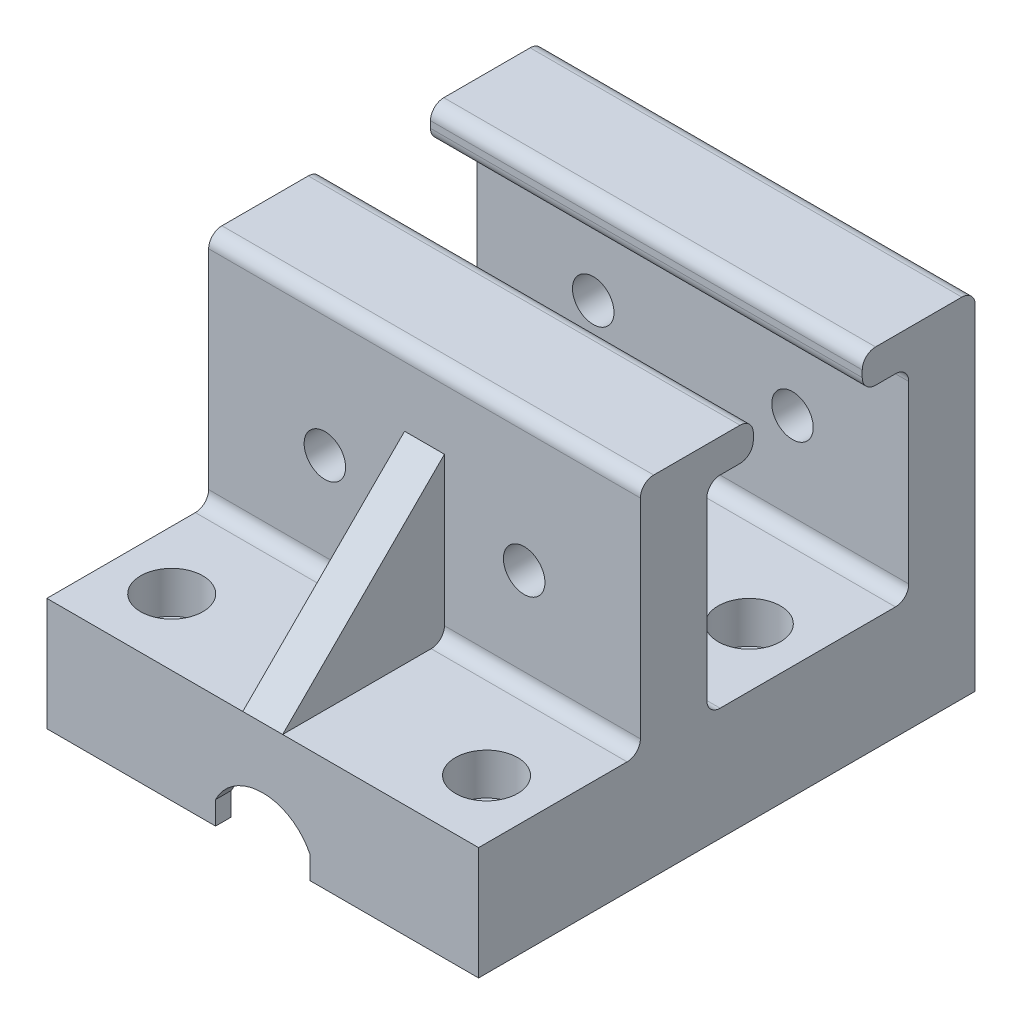
SolidWorks part; units mm, degrees
ref_plane "Front Plane" through (0, 0, 0) normal (0, 0, 1) x (1, 0, 0)
ref_plane "Top Plane" through (0, 0, 0) normal (0, 1, 0) x (1, 0, 0)
ref_plane "Right Plane" through (0, 0, 0) normal (1, 0, 0) x (0, 0, -1)
sketch "Sketch1" plane through (0, 0, 0) normal (0, 0, 1) x (1, 0, 0)
  line L0 (0, 0) -> (0, 28.1718) construction
  line L1 (15.875, 0) -> (41.275, 0)
  line L2 (41.275, 0) -> (41.275, 21.59)
  line L3 (41.275, 21.59) -> (-41.275, 21.59)
  line L4 (-41.275, 0) -> (-41.275, 21.59)
  line L5 (-15.875, 0) -> (-41.275, 0)
  arc A0 (15.875, 0) -> (-15.875, 0) centre (0, 0) ccw
  point P9 (0, 21.59)
  dimension "D1" = 31.75
  dimension "D2" = 25.4
  dimension "D3" = 21.59
extrude "Boss-Extrude1" add sketch "Sketch1" along normal blind 94.9452
sketch "Sketch2" plane through (0, 0, 0) normal (0, 0, -1) x (-1, 0, 0)
  circle A0 centre (0, 0) radius 18.923
  dimension "D1" = 37.846
extrude "Cut-Extrude1" cut sketch "Sketch2" against normal blind 56.9976
sketch "Sketch3" plane through (0, 0, 94.9452) normal (0, 0, 1) x (1, 0, 0)
  line L0 (-9.017, 4.3994) -> (-9.017, 0)
  line L1 (9.017, 4.3994) -> (9.017, 0)
  line L2 (-15.875, 0) -> (-9.017, 0)
  line L3 (15.875, 0) -> (9.017, 0)
  arc A0 (15.875, 0) -> (-15.875, 0) centre (0, 0) ccw
  arc A1 (9.017, 4.3994) -> (-9.017, 4.3994) centre (0, 0) ccw
  arc A2 (15.875, 0) -> (-15.875, 0) centre (0, 0) ccw construction
  dimension "D1" = 20.066
  dimension "D2" = 18.034
extrude "Boss-Extrude2" add sketch "Sketch3" against normal blind 2.9972
ref_plane "Plane1" through (0, 0, 0) normal (1, 0, 0) x (0, 0, -1)
sketch "Sketch6" plane through (0, 0, 0) normal (1, 0, 0) x (0, 0, -1)
  line L0 (-32.004, 21.59) -> (-32.004, 62.0795) construction
  line L1 (-94.9452, 21.59) -> (0, 21.59) construction
  line L2 (0, 21.59) -> (0, 66.548)
  line L3 (0, 66.548) -> (-21.59, 66.548)
  line L4 (-21.59, 66.548) -> (-21.59, 60.198)
  line L5 (-21.59, 60.198) -> (-12.7, 60.198)
  line L6 (-12.7, 60.198) -> (-12.7, 21.59)
  line L7 (-12.7, 21.59) -> (0, 21.59)
  line L8 (-51.308, 21.59) -> (-64.008, 21.59)
  line L9 (-51.308, 60.198) -> (-51.308, 21.59)
  line L10 (-42.418, 60.198) -> (-51.308, 60.198)
  line L11 (-42.418, 66.548) -> (-42.418, 60.198)
  line L12 (-64.008, 66.548) -> (-42.418, 66.548)
  line L13 (-64.008, 21.59) -> (-64.008, 66.548)
  line L14 (0, 0) -> (0, 21.59) construction
  dimension "D1" = 38.608
  dimension "D2" = 12.7
  dimension "D3" = 6.35
  dimension "D4" = 8.89
  dimension "D5" = 38.608
extrude "Boss-Extrude3" add sketch "Sketch6" along normal up to surface and the other way up to surface up to face at (41.275, 10.795, 47.4726) other way up to face at (-41.275, 10.795, 47.4726)
hole_wizard "Hole2" positions "Sketch7" profile "Sketch9" legacy end condition through all
sketch "Sketch7" plane through (0, 21.59, 0) normal (0, 1, 0) x (1, 0, 0)
  line L0 (41.275, -32.004) -> (-41.275, -32.004) construction
  line L1 (41.275, -51.308) -> (41.275, -12.7) construction
  line L2 (-41.275, -51.308) -> (-41.275, -12.7) construction
  line L4 (-30.099, -94.9452) -> (-30.099, -32.004) construction
  line L5 (41.275, -94.9452) -> (-41.275, -94.9452) construction
  line L8 (-41.275, -94.9452) -> (-41.275, 0) construction
  line L9 (-18.923, 0) -> (-18.923, -56.9976) construction
  point P0 (-30.099, -32.004)
  point P2 (-30.099, -82.2452)
  point P25 (-30.099, -83.143)
  dimension "D1" = 12.7
sketch "Sketch9" plane through (-30.099, 21.59, 32.004) normal (1, 0, 0) x (0, 0, 1)
  line L0 (0, 0) -> (0, 21.59)
  line L1 (0, 21.59) -> (3.9688, 21.59)
  line L2 (3.9688, 21.59) -> (3.9688, 7.9375)
  line L3 (3.9688, 7.9375) -> (5.9531, 7.9375)
  line L4 (5.9531, 7.9375) -> (5.9531, 0)
  line L5 (5.9531, 0) -> (0, 0)
  line L6 (0, 110) -> (0, -10) construction
  dimension "Diameter" = 7.9375
  dimension "Depth" = 21.59
  dimension "C-Bore Diameter" = 11.9062
  dimension "C-Bore Depth" = 7.9375
mirror "Mirror2" about plane through (0, 0, 0) normal (1, 0, 0) of "Hole2"
sketch "Sketch10" plane through (0, 0, 0) normal (0, 0, 1) x (1, 0, 0)
  line L0 (-41.275, 40.894) -> (41.275, 40.894) construction
  line L1 (-41.275, 21.59) -> (-41.275, 66.548) construction
  line L2 (41.275, 21.59) -> (41.275, 66.548) construction
  line L3 (41.275, 21.59) -> (-41.275, 21.59) construction
  line L4 (41.275, 60.198) -> (-41.275, 60.198) construction
  line L5 (0, 66.548) -> (0, 40.894) construction
  line L6 (41.275, 66.548) -> (-41.275, 66.548) construction
  circle A0 centre (-19.05, 40.894) radius 3.9688
  circle A1 centre (19.05, 40.894) radius 3.9688
  dimension "D1" = 38.1
  dimension "D2" = 7.9375
extrude "Cut-Extrude3" cut sketch "Sketch10" against normal through all and the other way through all
sketch "Sketch11" plane through (0, 0, 0) normal (1, 0, 0) x (0, 0, -1)
  line L0 (-94.9452, 21.59) -> (-64.008, 52.5272)
  line L1 (-64.008, 21.59) -> (-64.008, 66.548) construction
  line L2 (-94.9452, 21.59) -> (-64.008, 21.59) construction
  dimension "D1" = 45
rib "Rib1" sketch "Sketch11" sketch "Sketch11" thickness 7.62 extrusion direction parallel to sketch draft on no parameters "D1"=7.62
fillet "Fillet1" radius 2.54 12 edges at (0, 60.198, 42.418) (0, 66.548, 42.418) (0, 66.548, 21.59) (0, 60.198, 21.59) (0, 60.198, 12.7) (0, 60.198, 51.308) (22.5425, 21.59, 64.008) (-22.5425, 21.59, 64.008) (0, 21.59, 51.308) (0, 21.59, 12.7) (0, 66.548, 0) (0, 66.548, 64.008)
